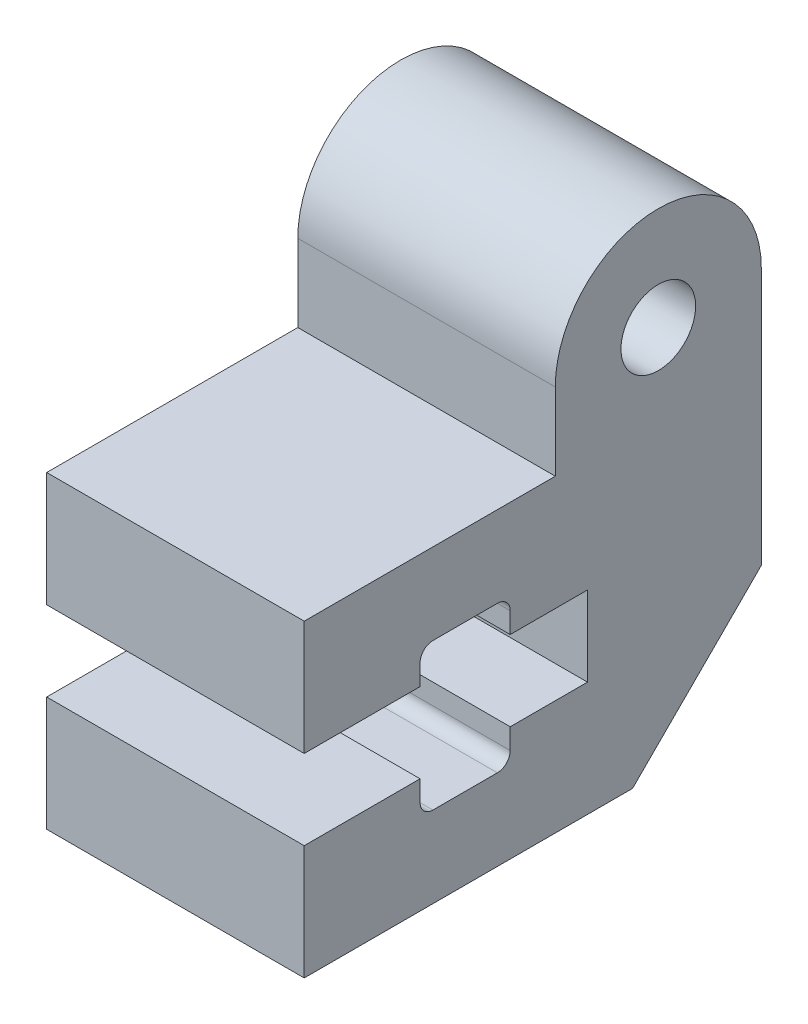
SolidWorks part; units mm, degrees
ref_plane "Front Plane" through (0, 0, 0) normal (0, 0, 1) x (1, 0, 0)
ref_plane "Top Plane" through (0, 0, 0) normal (0, 1, 0) x (1, 0, 0)
ref_plane "Right Plane" through (0, 0, 0) normal (1, 0, 0) x (0, 0, -1)
sketch "Sketch1" plane through (0, 0, 0) normal (1, 0, 0) x (0, 0, -1)
  line L0 (0, 0) -> (9.75, 0)
  line L1 (9.75, 0) -> (9.75, 3)
  line L2 (13.75, 3) -> (58.2289, -31.7907) construction
  line L3 (17.75, 3) -> (17.75, -2.6524)
  line L4 (17.75, -2.6524) -> (60.2979, -28.3674)
  line L5 (0, -6) -> (11.2315, -6) construction
  line L6 (56.1599, -35.2141) -> (17.75, -12)
  line L7 (17.75, -12) -> (0, -12)
  line L8 (0, -12) -> (0, 0)
  line L9 (17.75, -2.6524) -> (17.75, -12) construction
  arc A0 (17.75, 3) -> (9.75, 3) centre (13.75, 3) ccw
  arc A1 (56.1599, -35.2141) -> (60.2979, -28.3674) centre (58.2289, -31.7907) ccw
  circle A2 centre (13.75, 3) radius 1.45
  circle A3 centre (58.2289, -31.7907) radius 1.45
  circle A4 centre (58.2289, -31.7907) radius 2.25 construction
  dimension "D1" = 4
  dimension "D2" = 4
  dimension "D8" = 2.9
  dimension "D9" = 2.9
  dimension "D5" = 12
  dimension "D6" = 8
  dimension "D7" = 8
  dimension "D10" = 9
  dimension "D11" = 13.75
extrude "Boss-Extrude1" add sketch "Sketch1" along normal blind 10
sketch "Sketch2" plane through (10, 0, 0) normal (1, 0, 0) x (0, 0, -1)
  line L0 (0, -6) -> (11, -6) construction
  line L1 (0, 0) -> (0, -12) construction
  line L2 (0, -4.45) -> (11, -4.45) construction
  line L3 (11, -4.45) -> (11, -7.55) construction
  line L4 (0, -7.55) -> (0, -4.45)
  line L5 (0, -4.45) -> (4.5, -4.45)
  line L6 (4.5, -4.45) -> (4.5, -3.65)
  line L7 (5, -3.15) -> (7.5, -3.15)
  line L8 (8, -3.65) -> (8, -4.45)
  line L9 (8, -4.45) -> (11, -4.45)
  line L10 (11, -4.45) -> (11, -7.55)
  line L11 (0, -7.55) -> (11, -7.55) construction
  line L12 (8, -7.55) -> (11, -7.55)
  line L13 (8, -8.35) -> (8, -7.55)
  line L14 (5, -8.85) -> (7.5, -8.85)
  line L15 (4.5, -7.55) -> (4.5, -8.35)
  line L16 (0, -7.55) -> (4.5, -7.55)
  arc A0 (7.5, -3.15) -> (8, -3.65) centre (7.5, -3.65) cw
  arc A1 (4.5, -3.65) -> (5, -3.15) centre (5, -3.65) cw
  arc A2 (4.5, -8.35) -> (5, -8.85) centre (5, -8.35) ccw
  arc A3 (7.5, -8.85) -> (8, -8.35) centre (7.5, -8.35) ccw
  point P12 (8, -3.15)
  point P15 (4.5, -3.15)
  point P26 (4.5, -8.85)
  point P27 (8, -8.85)
  dimension "D6" = 0.5
  dimension "D1" = 11
  dimension "D2" = 1.55
  dimension "D3" = 2.85
  dimension "D4" = 3.5
  dimension "D5" = 8
extrude "Cut-Extrude1" cut sketch "Sketch2" against normal through all
sketch "Sketch3" plane through (10, 0, 0) normal (1, 0, 0) x (0, 0, -1)
  line L0 (17.75, -7) -> (12.75, -12)
  line L1 (12.75, -12) -> (0, -12)
  line L2 (0, -12) -> (0, 0)
  line L3 (0, 0) -> (17.75, 43)
  line L4 (17.75, 43) -> (17.75, -7)
  line L5 (0, -12) -> (17.75, -12) construction
  line L6 (17.75, -2.6524) -> (17.75, 3) construction
  dimension "D1" = 50
  dimension "D2" = 135
  dimension "D3" = 5
extrude "Cut-Extrude2" cut sketch "Sketch3" against normal blind 10 flip side to cut
equation "\"X-ROD-SPACING\"=45"
equation "\"Y-ROD-SPACING\"=75"
equation "\"Z-ROD-SPACING\"=17.5"
equation "\"Y-BED-OFFSET\"=2"
equation "\"Y-BED-ROD-INSET\"=3.5"
equation "\"Y-BED-SCREW-SPACING\"=209"
equation "\"Y-BED-SCREW-CUTOUT-SLOT-HEIGHT\"=2"
equation "\"T-SLOT-NUT-FILLET-RADIUS\"=0.5"
equation "\"T-SLOT-SCREW-SHAFT-RADIUS\"=1.55"
equation "\"T-SLOT-SCREW-SHAFT-CUTOUT-LENGTH\"=11.0"
equation "\"T-SLOT-NUT-DEPTH\"=3.5"
equation "\"T-SLOT-NUT-WIDTH\"=2.85"
equation "\"T-SLOT-NUT-END-DISTANCE\"=8"
equation "\"ACRYLIC-THICKNESS\"=10"
equation "\"ACRYLIC-THICKNESS2\"=4.5"
equation "\"ACRYLIC-TAB-CUTOUT-SIZE\"=\"ACRYLIC-THICKNESS\"+\"ACRYLIC-TAB-TOLERANCE\"*2"
equation "\"ACRYLIC-TAB-TOLERANCE\"=-.05"
equation "\"KERF\"=0.05"
equation "\"ACRYLIC-THICKNESS-TAB-CUTOUT-WIDTH\"=\"ACRYLIC-THICKNESS\"-\"KERF\"*2"
equation "\"ACRYLIC-THICKNESS-TAB-CUTOUT-HEIGHT\"=\"ACRYLIC-TAB-WIDTH\"-\"KERF\"*4"
equation "\"ACRYLIC-THICKNESS2-TAB-CUTOUT-WIDTH\"=\"ACRYLIC-THICKNESS2\"-\"KERF\"*2"
equation "\"ACRYLIC-THICKNESS2-TAB-CUTOUT-HEIGHT\"=\"ACRYLIC-TAB-WIDTH\"-\"KERF\"*4"
equation "\"ACRYLIC-TAB-WIDTH\"=\"ACRYLIC-THICKNESS\""
equation "\"ACRYLIC-M3-HOLE\"=2.9"
equation "\"SMOOTHROD-CAP-SCREW-DISTANCE\"=20"
equation "\"FRAME-WIDTH-INNER\"=370"
equation "\"NEMA17-HOLE-SPACING\"=31"
equation "\"NEMA17-CENTRAL-CUTOUT\"=22.5"
equation "\"Z-BRACKET-REACH\"=55"
equation "\"Z-ROD-INSET\"=16"
equation "\"TOP-BRACKET-SPACING\"=40"
equation "\"SMOOTHROD-X-LENGTH\"=350"
equation "\"SMOOTHROD-Y-LENGTH\"=350"
equation "\"SMOOTHROD-Z-LENGTH\"=350"
equation "\"SMOOTHROD-TIGHTENING-HEADROOM\"=.25"
equation "\"LEADSCREW-Z-LENGTH\"=300"
equation "\"SCREW-LENGTH-FRAME\"=\"ACRYLIC-THICKNESS\" + 10"
equation "\"SCREW-LENGTH-MOTOR\"=\"ACRYLIC-THICKNESS\" + 5"
equation "\"SCREW-LENGTH-EXTRUDER\"=28"
equation "\"SCREW-HEAD-RADIUS\"=6"
equation "\"PRINTED-M3-HOLE\"=3.5"
equation "\"PRINTED-X-SMOOTHROD-DIAMETER\"=9.4"
equation "\"PRINTED-X-SMOOTHROD-CUTOUT\"=10"
equation "\"PRINTED-X-BASE-HEIGHT\"=10"
equation "\"PRINTED-LM8UU-CUTOUT-SIZE\"=15.5"
equation "\"PRINTED-LM8UU-CUTOUT-LENGTH\"=24.5"
equation "\"PRINTED-X-IDLER-HEIGHT\"=16"
equation "\"PRINTED-M3-NUT-AF\"=6.25"
equation "\"PSU-MOUNTING-WIDTH\"=95"
equation "\"PSU-MOUNTING-HEIGHT\"=177"
equation "\"Y-BELT-TO-ROD-DISTANCE\"=20"
equation "\"SPOOL-HOLDER-ROD-SPACING\"=150"
equation "\"ACRYLIC-X-CARRIAGE-WIDTH\"=55"
equation "\"ACRYLIC-X-CARRIAGE-HEIGHT\"=75"
equation "\"ACRYLIC-X-CARRIAGE-LM8UU-CUTOUT-WIDTH\"=24.25"
equation "\"ACRYLIC-X-CARRIAGE-LM8UU-CUTOUT-HEIGHT\"=11.0"
equation "\"ACRYLIC-X-CARRIAGE-SCREW-SPACING-X\"=15"
equation "\"ACRYLIC-X-CARRIAGE-SCREW-SPACING-Y\"=33"
equation "\"ACRYLIC-X-CARRIAGE-CENTER-TAB-SPACING\"=14"
equation "\"ACRYLIC-X-CARRIAGE-EXTRUDER-OFFSET\"=26"
equation "\"ACRYLIC-X-CARRIAGE-EXTRUDER-ANGLE\"=90"
equation "\"ACRYLIC-X-CARRIAGE-EXTRUDER-SHELF-DEPTH\"=\"ACRYLIC-X-CARRIAGE-EXTRUDER-OFFSET\" + 28"
equation "\"ACRYLIC-X-CARRIAGE-EXTRUDER-BRACE-SPACING\"=23"
equation "\"ACRYLIC-X-CARRIAGE-EXTRUDER-BRACE-TAB-OFFSET\"=20"
equation "\"ACRYLIC-X-CARRIAGE-EXTRUDER-BRACE-HEIGHT\"=35"
equation "\"ACRYLIC-X-CARRIAGE-EXTRUDER-BRACE-SCREW-SPACING\"=22"
equation "\"ACRYLIC-X-CARRIAGE-DUAL-WIDTH-MULTIPLIER\"=1.65"
equation "\"ACRYLIC-X-CARRIAGE-DUAL-HOTEND-SPACING\"=42"
equation "\"ACRYLIC-X-CARRIAGE-DUAL-WIDTH\"=75"
equation "\"ACRYLIC-X-CARRIAGE-DUAL-FAN-OFFSET\"=52"
equation "\"ACRYLIC-X-CARRIAGE-DUAL-FAN-HEIGHT\"=20"
equation "\"ACRYLIC-X-CARRIAGE-DUAL-HOTEND-SEPARATION\"=36"
equation "\"ACRYLIC-X-CARRIAGE-DUAL-MOUNT-PLATE-DEPTH\"=75"
equation "\"ACRYLIC-X-CARRIAGE-DUAL-MOUNT-BRACE-WIDTH\"=33"
equation "\"ACRYLIC-X-CARRIAGE-DUAL-MOUNT-SCREW-WIDTH\"=40"
equation "\"BLOWER-FAN-WIDTH\"=15"
equation "\"D8@Sketch1\"=\"ACRYLIC-M3-HOLE\""
equation "\"D9@Sketch1\"=\"ACRYLIC-M3-HOLE\""
equation "\"D1@Boss-Extrude1\"=\"ACRYLIC-THICKNESS\""
equation "\"D1@Sketch2\"=\"T-SLOT-SCREW-SHAFT-CUTOUT-LENGTH\""
equation "\"D2@Sketch2\"=\"T-SLOT-SCREW-SHAFT-RADIUS\""
equation "\"D3@Sketch2\"=\"T-SLOT-NUT-WIDTH\""
equation "\"D4@Sketch2\"=\"T-SLOT-NUT-DEPTH\""
equation "\"D5@Sketch2\"=\"T-SLOT-NUT-END-DISTANCE\""
equation "\"D6@Sketch2\"=\"T-SLOT-NUT-FILLET-RADIUS\""
